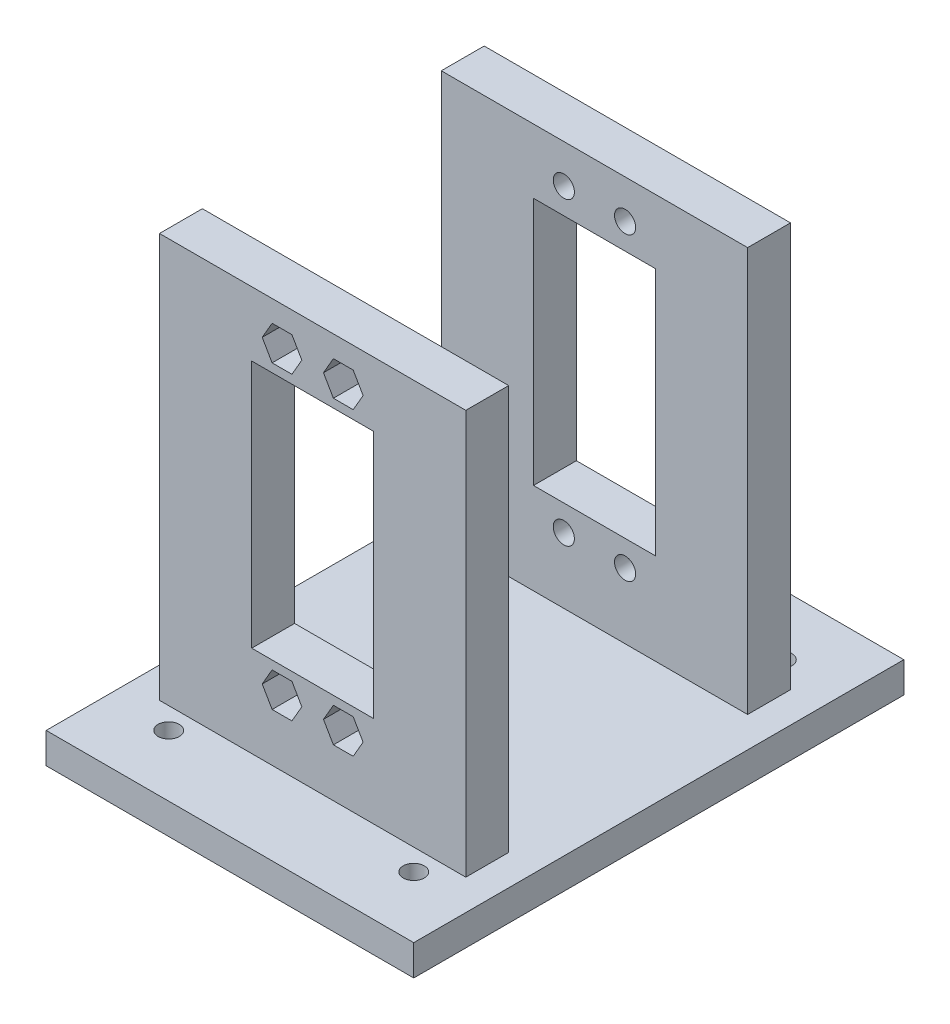
SolidWorks part; units mm, degrees
material "PLA Makeshift"
ref_plane "Front Plane" through (0, 0, 0) normal (0, 0, 1) x (1, 0, 0)
ref_plane "Top Plane" through (0, 0, 0) normal (0, 1, 0) x (1, 0, 0)
ref_plane "Right Plane" through (0, 0, 0) normal (1, 0, 0) x (0, 0, -1)
sketch "Sketch1" plane through (0, 0, 0) normal (0, 1, 0) x (1, 0, 0)
  line L1 (-30, -40) -> (30, -40)
  line L2 (-30, -40) -> (-30, 40)
  line L3 (-30, 40) -> (30, 40)
  line L4 (30, -40) -> (30, 40)
  line L5 (-30, -40) -> (30, 40) construction
  line L6 (-30, 40) -> (30, -40) construction
  point P0 (0, 0)
  dimension "D1" = 80
  dimension "D2" = 60
extrude "Boss-Extrude1" add sketch "Sketch1" along normal mid plane 5
sketch "Sketch2" plane through (0, 2.5, 0) normal (0, 1, 0) x (1, 0, 0)
  line L0 (30, -40) -> (30, 40) construction
  line L2 (-30, 40) -> (-30, -40) construction
  line L3 (-30, -40) -> (30, -40) construction
  circle A0 centre (-20, 30) radius 1.725
  circle A1 centre (20, 30) radius 1.725
  circle A2 centre (20, -30) radius 1.725
  circle A3 centre (-20, -30) radius 1.725
  point P14 (0, 0)
  dimension "D1" = 3.45
  dimension "D2" = 40
  dimension "D3" = 10
  dimension "D4" = 60
  dimension "D5" = 60
  dimension "D6" = 40
  dimension "D7" = 10
  dimension "D8" = 10
  dimension "D9" = 10
extrude "Cut-Extrude1" cut sketch "Sketch2" against normal through all
ref_plane "Plane1" through (0, 0, 19.5) normal (0, 0, 1) x (1, 0, 0)
sketch "Sketch3" plane through (0, 0, 19.5) normal (0, 0, 1) x (1, 0, 0)
  line L1 (-25, 2.5) -> (25, 2.5)
  line L2 (-25, 2.5) -> (-25, 68.5)
  line L3 (-25, 68.5) -> (25, 68.5)
  line L4 (25, 2.5) -> (25, 68.5)
  point P4 (0, 0)
  point P6 (0, 0)
  dimension "D1" = 50
  dimension "D2" = 25
  dimension "D3" = 66
  dimension "D4" = 2.5
extrude "Boss-Extrude2" add sketch "Sketch3" along normal blind 7
mirror "Mirror1" about plane through (0, 0, 0) normal (0, 0, 1) of "Boss-Extrude2"
sketch "Sketch4" plane through (0, 0, 26.5) normal (0, 0, 1) x (1, 0, 0)
  line L1 (-9.95, 58) -> (9.95, 58)
  line L2 (-9.95, 58) -> (-9.95, 17.4)
  line L3 (-9.95, 17.4) -> (9.95, 17.4)
  line L4 (9.95, 58) -> (9.95, 17.4)
  dimension "D1" = 19.9
  dimension "D2" = 9.95
  dimension "D3" = 40.6
  dimension "D4" = 17.4
extrude "Cut-Extrude2" cut sketch "Sketch4" against normal through all
sketch "Sketch5" plane through (0, 0, 26.5) normal (0, 0, 1) x (1, 0, 0)
  circle A0 centre (-5, 62.2) radius 1.725
  circle A1 centre (5, 62.2) radius 1.725
  circle A2 centre (-5, 13.2) radius 1.725
  circle A3 centre (5, 13.2) radius 1.725
  dimension "D9" = 3.45
  dimension "D1" = 5
  dimension "D2" = 5
  dimension "D3" = 13.2
  dimension "D4" = 13.2
  dimension "D5" = 62.2
  dimension "D6" = 62.2
  dimension "D7" = 5
  dimension "D8" = 5
extrude "Cut-Extrude3" cut sketch "Sketch5" against normal through all
sketch "Sketch6" plane through (0, 0, 26.5) normal (0, 0, 1) x (1, 0, 0)
  line L1 (-1.7668, 62.2) -> (-3.3834, 65)
  line L2 (-3.3834, 65) -> (-6.6166, 65)
  line L3 (-6.6166, 65) -> (-8.2332, 62.2)
  line L4 (-8.2332, 62.2) -> (-6.6166, 59.4)
  line L5 (-6.6166, 59.4) -> (-3.3834, 59.4)
  line L6 (-3.3834, 59.4) -> (-1.7668, 62.2)
  line L7 (1.7668, 62.2) -> (3.3834, 59.4)
  line L8 (3.3834, 59.4) -> (6.6166, 59.4)
  line L9 (6.6166, 59.4) -> (8.2332, 62.2)
  line L10 (8.2332, 62.2) -> (6.6166, 65)
  line L11 (6.6166, 65) -> (3.3834, 65)
  line L12 (3.3834, 65) -> (1.7668, 62.2)
  line L13 (-1.7668, 13.2) -> (-3.3834, 16)
  line L14 (-3.3834, 16) -> (-6.6166, 16)
  line L15 (-6.6166, 16) -> (-8.2332, 13.2)
  line L16 (-8.2332, 13.2) -> (-6.6166, 10.4)
  line L17 (-6.6166, 10.4) -> (-3.3834, 10.4)
  line L18 (-3.3834, 10.4) -> (-1.7668, 13.2)
  line L19 (8.2332, 13.2) -> (6.6166, 16)
  line L20 (6.6166, 16) -> (3.3834, 16)
  line L21 (3.3834, 16) -> (1.7668, 13.2)
  line L22 (1.7668, 13.2) -> (3.3834, 10.4)
  line L23 (3.3834, 10.4) -> (6.6166, 10.4)
  line L24 (6.6166, 10.4) -> (8.2332, 13.2)
  circle A0 centre (-5, 62.2) radius 2.8 construction
  circle A1 centre (5, 62.2) radius 2.8 construction
  circle A2 centre (-5, 13.2) radius 2.8 construction
  circle A3 centre (5, 13.2) radius 2.8 construction
extrude "Cut-Extrude4" cut sketch "Sketch6" against normal blind 4.2
mirror "Mirror3" about plane through (0, 0, 0) normal (0, 0, 1) of "Cut-Extrude4"
